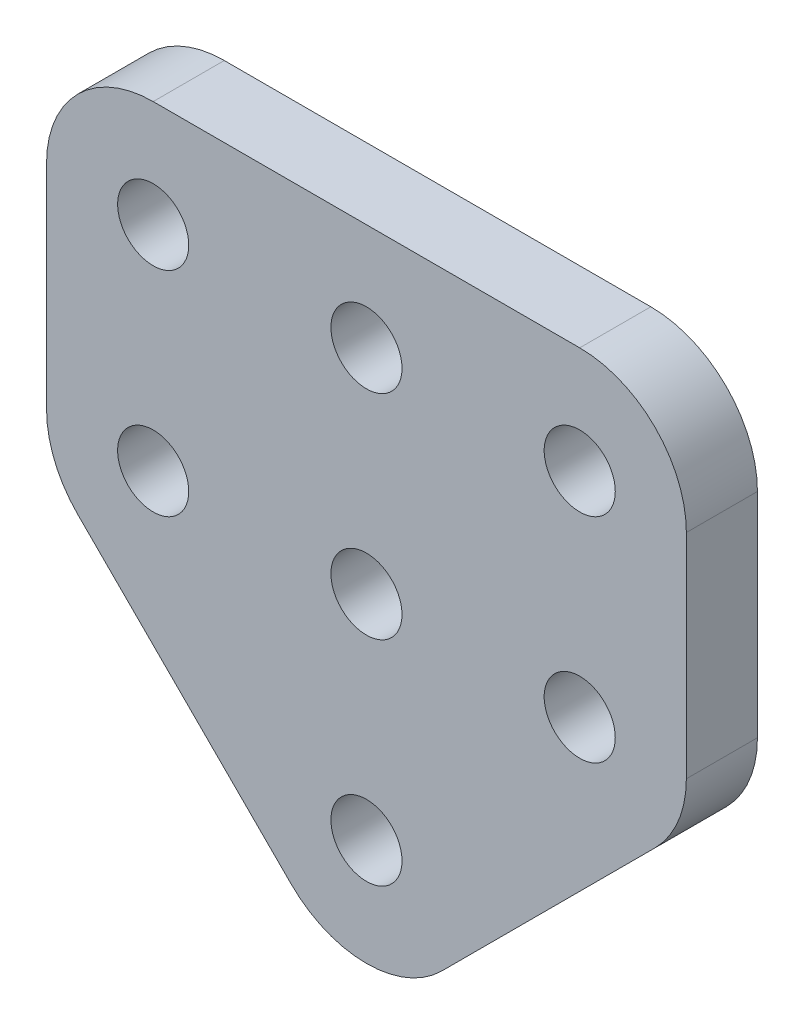
SolidWorks part; units mm, degrees
ref_plane "Alzado" through (0, 0, 0) normal (0, 0, 1) x (1, 0, 0)
ref_plane "Planta" through (0, 0, 0) normal (0, 1, 0) x (1, 0, 0)
ref_plane "Vista lateral" through (0, 0, 0) normal (1, 0, 0) x (0, 0, -1)
sketch "Model" plane through (0, 0, 0) normal (0, 0, 1) x (1, 0, 0)
  line L0 (174.2271, 213.1787) -> (174.2271, 204.1787)
  line L1 (196.7271, 217.6787) -> (178.7271, 217.6787)
  line L2 (201.2271, 213.1787) -> (201.2271, 204.1787)
  line L3 (190.909, 191.9967) -> (199.909, 200.9967)
  line L4 (184.5451, 191.9967) -> (175.5451, 200.9967)
  circle A0 centre (187.7271, 204.1787) radius 1.5
  circle A1 centre (178.7271, 204.1787) radius 1.5
  circle A2 centre (187.7271, 213.1787) radius 1.5
  circle A3 centre (178.7271, 213.1787) radius 1.5
  circle A4 centre (196.7271, 213.1787) radius 1.5
  circle A5 centre (187.7271, 195.1787) radius 1.5
  circle A6 centre (196.7271, 204.1787) radius 1.5
  arc A7 (184.5451, 191.9967) -> (190.909, 191.9967) centre (187.7271, 195.1787) ccw
  arc A8 (199.909, 200.9967) -> (201.2271, 204.1787) centre (196.7271, 204.1787) ccw
  arc A9 (174.2271, 204.1787) -> (175.5451, 200.9967) centre (178.7271, 204.1787) ccw
  arc A10 (178.7271, 217.6787) -> (174.2271, 213.1787) centre (178.7271, 213.1787) ccw
  arc A11 (201.2271, 213.1787) -> (196.7271, 217.6787) centre (196.7271, 213.1787) ccw
extrude "Saliente-Extruir1" add sketch "Model" along normal blind 3
